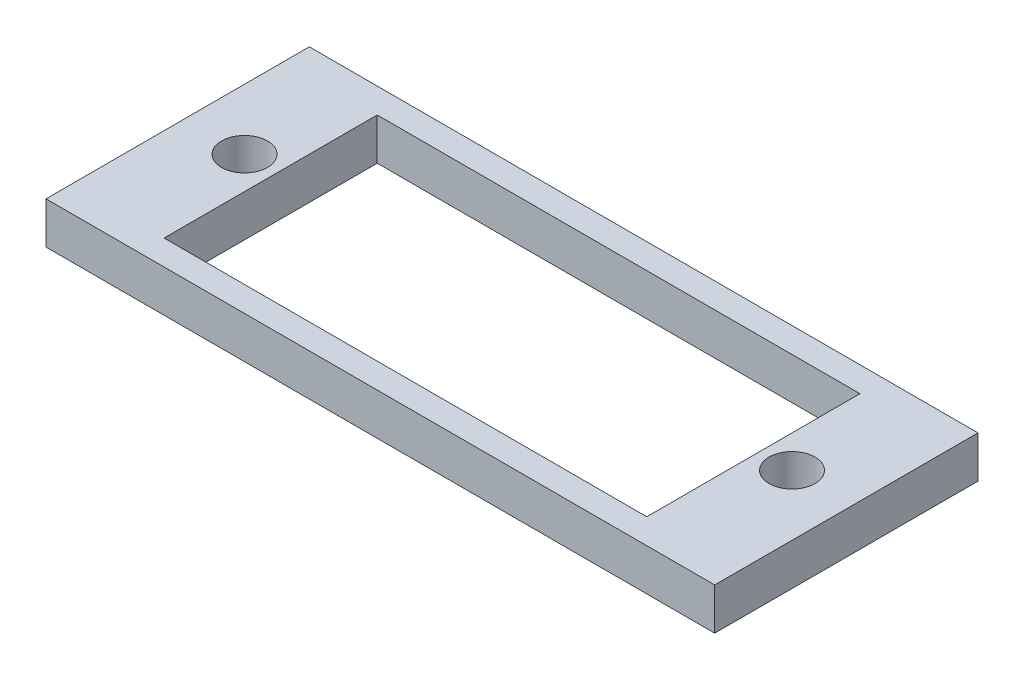
SolidWorks part; units mm, degrees
ref_plane "Piano frontale" through (0, 0, 0) normal (0, 0, 1) x (1, 0, 0)
ref_plane "Piano superiore" through (0, 0, 0) normal (0, 1, 0) x (1, 0, 0)
ref_plane "Piano destro" through (0, 0, 0) normal (1, 0, 0) x (0, 0, -1)
sketch "Schizzo1" plane through (0, 0, 0) normal (0, 1, 0) x (1, 0, 0)
  line L1 (0, 12.6) -> (32, 12.6)
  line L2 (0, 12.6) -> (0, 0)
  line L3 (0, 0) -> (32, 0)
  line L4 (32, 12.6) -> (32, 0)
  line L5 (4.45, 11.4) -> (27.55, 11.4)
  line L6 (4.45, 11.4) -> (4.45, 1.2)
  line L7 (4.45, 1.2) -> (27.55, 1.2)
  line L8 (27.55, 11.4) -> (27.55, 1.2)
  circle A0 centre (2.9, 6.6) radius 1.1
  circle A1 centre (29.1, 6.6) radius 1.1
  point P14 (16, 11.4)
  dimension "D3" = 6
  dimension "D4" = 6
  dimension "D5" = 2.9
  dimension "D6" = 2.9
  dimension "D7" = 2.2
  dimension "2.2" = 2.2
  dimension "D1" = 12.6
  dimension "D2" = 32
  dimension "D9" = 1.2
  dimension "D10" = 23.1
  dimension "D11" = 16
  dimension "D12" = 1.2
extrude "Estrusione-Estrusione1" add sketch "Schizzo1" along normal blind 2
